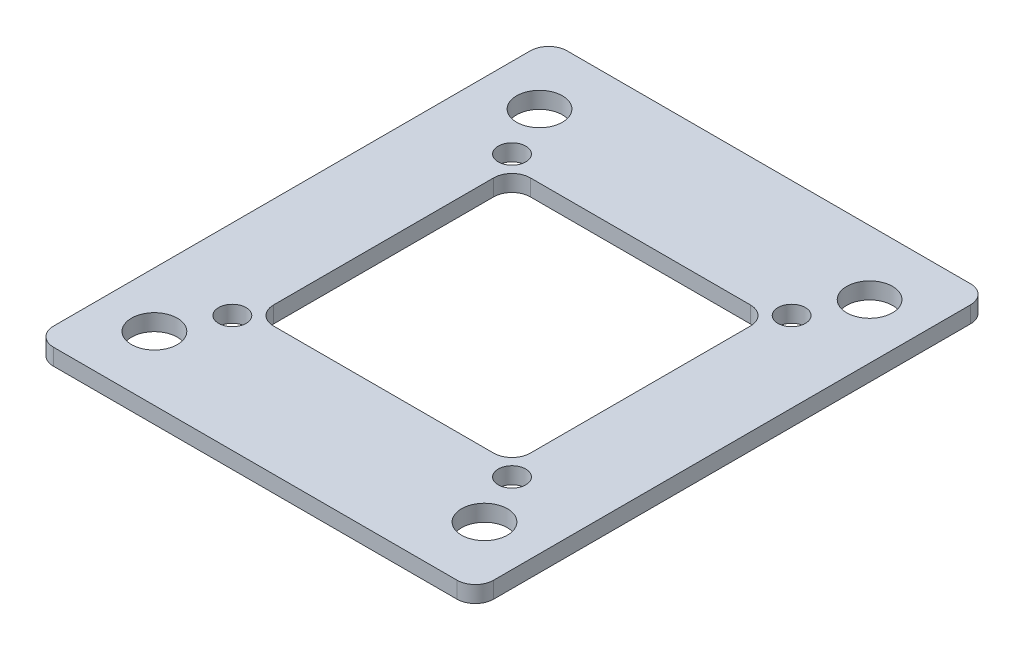
SolidWorks part; units mm, degrees
ref_plane "前视基准面" through (0, 0, 0) normal (0, 0, 1) x (1, 0, 0)
ref_plane "上视基准面" through (0, 0, 0) normal (0, 1, 0) x (1, 0, 0)
ref_plane "右视基准面" through (0, 0, 0) normal (1, 0, 0) x (0, 0, -1)
other "Configuration Table"
sketch "草图1" plane through (0, 0, 0) normal (0, 1, 0) x (1, 0, 0)
  line L1 (-24, -28) -> (24, -28)
  line L2 (-24, -28) -> (-24, 28)
  line L3 (-24, 28) -> (24, 28)
  line L4 (24, -28) -> (24, 28)
  line L5 (0, 28) -> (0, -28) construction
  line L6 (-24, 0) -> (24, 0) construction
  circle A0 centre (-18, 21) radius 2.5
  circle A1 centre (18, 21) radius 2.5
  circle A2 centre (18, -21) radius 2.5
  circle A3 centre (-18, -21) radius 2.5
  point P0 (0, 0)
  dimension "D3" = 5
  dimension "D4" = 21
  dimension "D5" = 18
  dimension "D1" = 48
  dimension "D2" = 56
extrude "凸台-拉伸1" add sketch "草图1" along normal blind 1.8
sketch "草图2" plane through (0, 1.8, 0) normal (0, 1, 0) x (1, 0, 0)
  line L0 (-1000, 0) -> (49000, 0) construction
  line L1 (0, -1000) -> (0, 49000) construction
  line L3 (-14, -14) -> (14, -14)
  line L4 (-14, -14) -> (-14, 14)
  line L5 (-14, 14) -> (14, 14)
  line L6 (14, -14) -> (14, 14)
  line L7 (0, 14) -> (0, -14) construction
  line L8 (-14, 0) -> (14, 0) construction
  circle A0 centre (15.25, 15.25) radius 1.5
  circle A1 centre (-15.25, 15.25) radius 1.5
  circle A2 centre (15.25, -15.25) radius 1.5
  circle A3 centre (-15.25, -15.25) radius 1.5
  point P4 (0, 0)
  dimension "D3" = 3
  dimension "D4" = 15.25
  dimension "D5" = 15.25
  dimension "D1" = 28
  dimension "D2" = 28
extrude "切除-拉伸1" cut sketch "草图2" against normal through all
fillet "圆角1" radius 2 8 edges at (14, 0.9, 14) (-14, 0.9, 14) (-14, 0.9, -14) (14, 0.9, -14) (-24, 0.9, 28) (24, 0.9, 28) (24, 0.9, -28) (-24, 0.9, -28)
